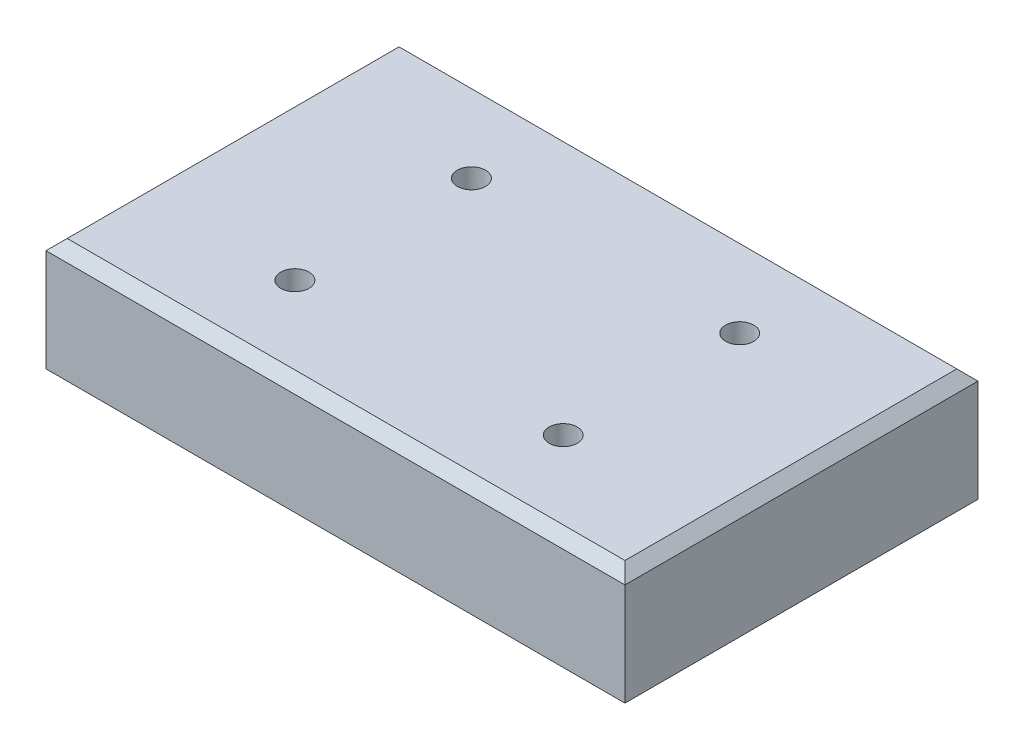
SolidWorks part; units mm, degrees
ref_plane "Front Plane" through (0, 0, 0) normal (0, 0, 1) x (1, 0, 0)
ref_plane "Top Plane" through (0, 0, 0) normal (0, 1, 0) x (1, 0, 0)
ref_plane "Right Plane" through (0, 0, 0) normal (1, 0, 0) x (0, 0, -1)
sketch "Sketch1" plane through (0, 0, 0) normal (0, 1, 0) x (1, 0, 0)
  line L1 (41, 25) -> (-41, 25)
  line L2 (41, 25) -> (41, -25)
  line L3 (41, -25) -> (-41, -25)
  line L4 (-41, 25) -> (-41, -25)
  line L5 (41, 25) -> (-41, -25) construction
  line L6 (41, -25) -> (-41, 25) construction
  point P0 (0, 0)
  dimension "D1" = 82
  dimension "D2" = 50
extrude "Boss-Extrude1" add sketch "Sketch1" along normal blind 16
chamfer "Chamfer1" distance 1.5 angle 45 4 edges at (41, 16, 0) (0, 16, -25) (0, 16, 25) (-41, 16, 0)
sketch "Sketch2" plane through (0, 16, 0) normal (0, 1, 0) x (1, 0, 0)
  line L0 (0, 23.5) -> (0, -23.5) construction
  line L1 (39.5, 23.5) -> (-39.5, 23.5) construction
  line L2 (-39.5, -23.5) -> (39.5, -23.5) construction
  line L3 (-39.5, 0) -> (39.5, 0) construction
  line L4 (-39.5, 23.5) -> (-39.5, -23.5) construction
  line L5 (39.5, -23.5) -> (39.5, 23.5) construction
  circle A0 centre (19.75, 12.5) radius 2
  circle A1 centre (-18.25, 12.5) radius 2
  circle A2 centre (19.75, -12.5) radius 2
  circle A3 centre (-18.25, -12.5) radius 2
  point P12 (19.75, 12.5)
  point P14 (-18.25, 12.5)
  point P17 (19.75, -12.5)
  point P19 (-18.25, -12.5)
  dimension "D1" = 4
  dimension "D2" = 38
  dimension "D3" = 25
  dimension "D4" = 19.75
hole_wizard "M4 Tapped Hole3" positions "Sketch2" profile "Sketch3" tap size "M4" standard "DIN"
sketch "Sketch3" plane through (-18.25, 16, 12.5) normal (1, 0, 0) x (0, 0, 1)
  line L0 (0, 0) -> (0, 11.0914)
  line L1 (0, 11.0914) -> (1.65, 10.1)
  line L2 (1.65, 10.1) -> (1.65, 8)
  line L3 (1.65, 8) -> (2, 8)
  line L4 (2, 8) -> (2, 0)
  line L5 (2, 0) -> (0, 0)
  line L10 (0, 11.0914) -> (-1.65, 10.1) construction
  line L11 (0, -6.35) -> (0, 107.95) construction
  dimension "Tap Drill Dia." = 3.3
  dimension "Tap Drill Depth" = 10.1
  dimension "Thread Major Dia." = 4
  dimension "Thread Depth" = 8
  dimension "Drill Angle" = 118
